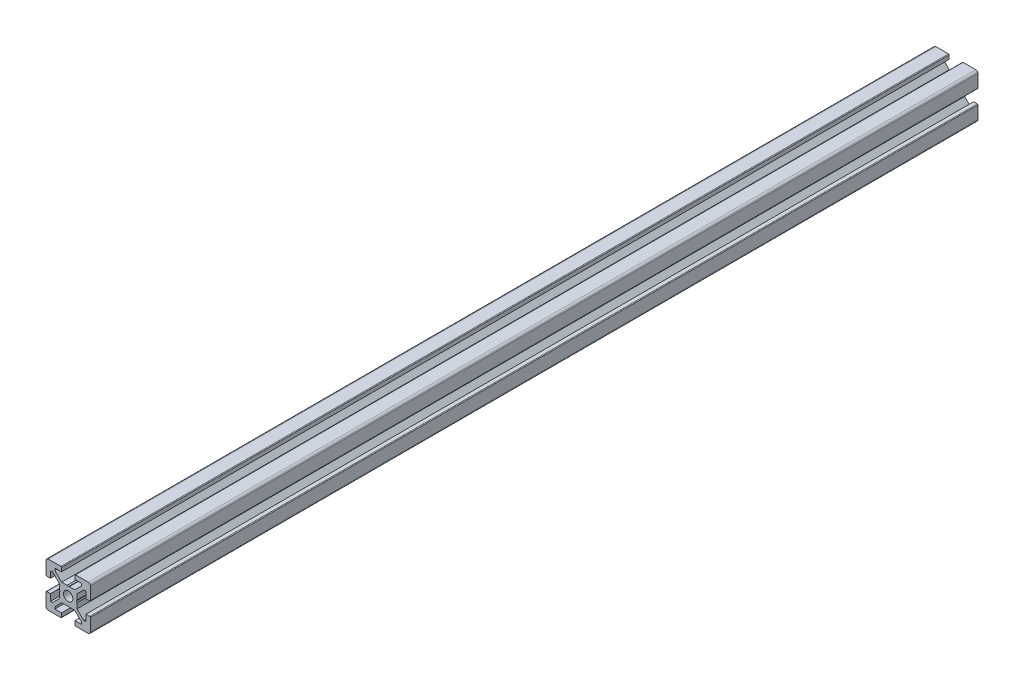
SolidWorks part; units mm, degrees
ref_plane "Front Plane" through (0, 0, 0) normal (0, 0, 1) x (1, 0, 0)
ref_plane "Top Plane" through (0, 0, 0) normal (0, 1, 0) x (1, 0, 0)
ref_plane "Right Plane" through (0, 0, 0) normal (1, 0, 0) x (0, 0, -1)
ref_plane "Plane1" through (0, 0, 0) normal (0, 0, 1) x (1, 0, 0)
sketch "Sketch1" plane through (0, 0, 0) normal (0, 0, 1) x (1, 0, 0)
  line L0 (-10, 9) -> (-10, 3.3)
  line L1 (-9.7, 3) -> (-8, 3)
  line L2 (-8, 3) -> (-8, 6)
  line L3 (-8, 6) -> (-7.0607, 6)
  line L4 (-7.0607, 6) -> (-4, 2.9393)
  line L5 (-4, 2.9393) -> (-4, 0.5196)
  line L6 (-4, 0.5196) -> (-3.7, 0)
  line L7 (-3.7, 0) -> (-4, -0.5196)
  line L8 (-4, -0.5196) -> (-4, -2.9393)
  line L9 (-4, -2.9393) -> (-7.0607, -6)
  line L10 (-7.0607, -6) -> (-8, -6)
  line L11 (-8, -6) -> (-8, -3)
  line L12 (-8, -3) -> (-9.7, -3)
  line L13 (-10, -3.3) -> (-10, -9)
  line L14 (-9, -10) -> (-3.3, -10)
  line L15 (-3, -9.7) -> (-3, -8)
  line L16 (-3, -8) -> (-6, -8)
  line L17 (-6, -8) -> (-6, -7.0607)
  line L18 (-6, -7.0607) -> (-2.9393, -4)
  line L19 (-2.9393, -4) -> (-0.5196, -4)
  line L20 (-0.5196, -4) -> (0, -3.7)
  line L21 (0, -3.7) -> (0.5196, -4)
  line L22 (0.5196, -4) -> (2.9393, -4)
  line L23 (2.9393, -4) -> (6, -7.0607)
  line L24 (6, -7.0607) -> (6, -8)
  line L25 (6, -8) -> (3, -8)
  line L26 (3, -8) -> (3, -9.7)
  line L27 (3.3, -10) -> (9, -10)
  line L28 (10, -9) -> (10, -3.3)
  line L29 (9.7, -3) -> (8, -3)
  line L30 (8, -3) -> (8, -6)
  line L31 (8, -6) -> (7.0606, -6)
  line L32 (7.0606, -6) -> (4, -2.9393)
  line L33 (4, -2.9393) -> (4, -0.5196)
  line L34 (4, -0.5196) -> (3.7, 0)
  line L35 (3.7, 0) -> (4, 0.5196)
  line L36 (4, 0.5196) -> (4, 2.9393)
  line L37 (4, 2.9393) -> (7.0607, 6)
  line L38 (7.0607, 6) -> (8, 6)
  line L39 (8, 6) -> (8, 3)
  line L40 (8, 3) -> (9.7, 3)
  line L41 (10, 3.3) -> (10, 9)
  line L42 (9, 10) -> (3.3, 10)
  line L43 (3, 9.7) -> (3, 8)
  line L44 (3, 8) -> (6, 8)
  line L45 (6, 8) -> (6, 7.0607)
  line L46 (6, 7.0607) -> (2.9393, 4)
  line L47 (2.9393, 4) -> (0.5196, 4)
  line L48 (0.5196, 4) -> (0, 3.7)
  line L49 (0, 3.7) -> (-0.5196, 4)
  line L50 (-0.5196, 4) -> (-2.9394, 4)
  line L51 (-2.9394, 4) -> (-6, 7.0606)
  line L52 (-6, 7.0606) -> (-6, 8)
  line L53 (-6, 8) -> (-3, 8)
  line L54 (-3, 8) -> (-3, 9.7)
  line L55 (-3.3, 10) -> (-9, 10)
  arc A0 (-10, 3.3) -> (-9.7, 3) centre (-9.7, 3.3) ccw
  arc A1 (-9.7, -3) -> (-10, -3.3) centre (-9.7, -3.3) ccw
  arc A2 (-10, -9) -> (-9, -10) centre (-9, -9) ccw
  arc A3 (-3.3, -10) -> (-3, -9.7) centre (-3.3, -9.7) ccw
  arc A4 (3, -9.7) -> (3.3, -10) centre (3.3, -9.7) ccw
  arc A5 (9, -10) -> (10, -9) centre (9, -9) ccw
  arc A6 (10, -3.3) -> (9.7, -3) centre (9.7, -3.3) ccw
  arc A7 (9.7, 3) -> (10, 3.3) centre (9.7, 3.3) ccw
  arc A8 (10, 9) -> (9, 10) centre (9, 9) ccw
  arc A9 (3.3, 10) -> (3, 9.7) centre (3.3, 9.7) ccw
  arc A10 (-3, 9.7) -> (-3.3, 10) centre (-3.3, 9.7) ccw
  arc A11 (-9, 10) -> (-10, 9) centre (-9, 9) ccw
extrude "Boss-Extrude1" add sketch "Sketch1" against normal blind 400
ref_plane "Plane2" through (0, 0, 0) normal (1, 0, 0) x (0, 0, -1)
sketch "Sketch2" plane through (0, 0, 0) normal (1, 0, 0) x (0, 0, -1)
  line L0 (0, 0) -> (0, 2.1)
  line L1 (0, 2.1) -> (400, 2.1)
  line L2 (400, 2.1) -> (400, 0)
  line L3 (400, 0) -> (0, 0)
  line L4 (400, 0) -> (0, 0) construction
revolve "Cut-Revolve1" cut sketch "Sketch2" angle 360 about L4
